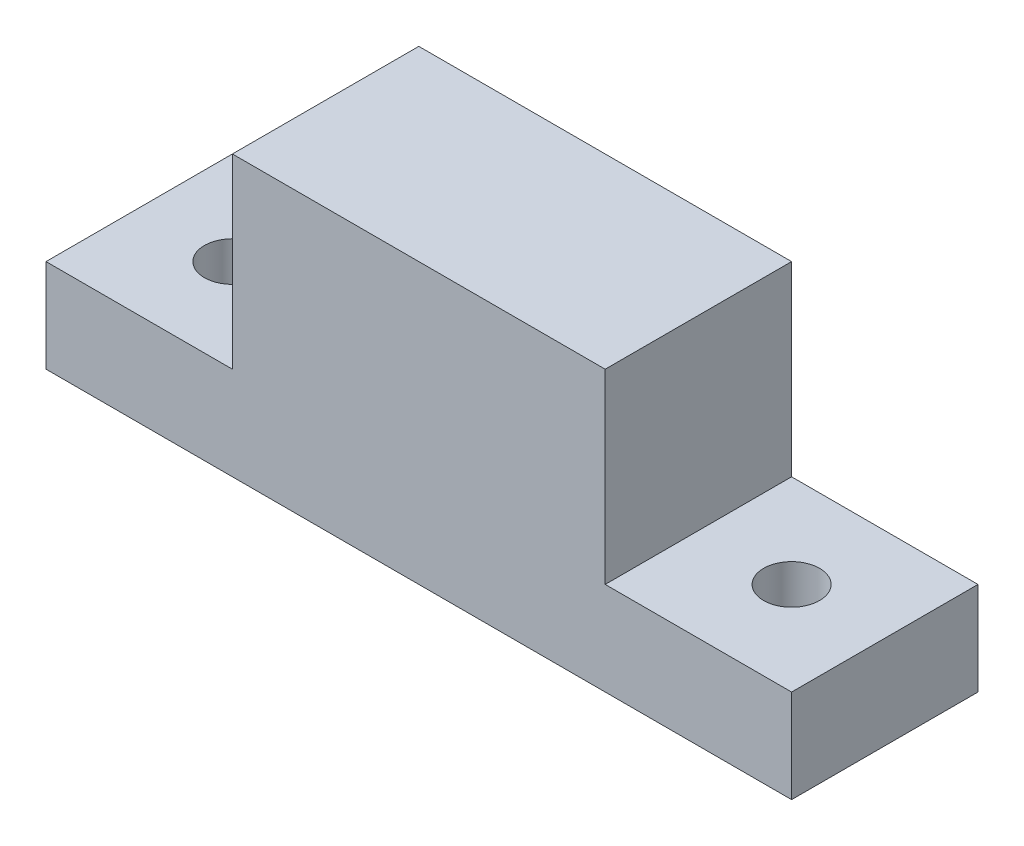
SolidWorks part; units mm, degrees
ref_plane "前视基准面" through (0, 0, 0) normal (0, 0, 1) x (1, 0, 0)
ref_plane "上视基准面" through (0, 0, 0) normal (0, 1, 0) x (1, 0, 0)
ref_plane "右视基准面" through (0, 0, 0) normal (1, 0, 0) x (0, 0, -1)
other "Configuration Table"
sketch "草图1" plane through (0, 0, 0) normal (0, 1, 0) x (1, 0, 0)
  line L0 (-30, 20.1444) -> (-30, -49979.8556) construction
  line L1 (-40, 10) -> (40, 10)
  line L2 (-40, 10) -> (-40, -10)
  line L3 (-40, -10) -> (40, -10)
  line L4 (40, 10) -> (40, -10)
  line L5 (-40, 10) -> (40, -10) construction
  line L6 (-40, -10) -> (40, 10) construction
  line L7 (30, 25.9846) -> (30, -49974.0154) construction
  line L8 (-40, 0) -> (49960, 0) construction
  line L9 (-34.4996, 5) -> (49965.5004, 5) construction
  line L10 (-32.2531, -5) -> (49967.7469, -5) construction
  circle A6 centre (-30, 0) radius 3
  circle A7 centre (30, 0) radius 3
  point P0 (0, 0)
  point P12 (-40, 0)
  dimension "D5" = 5
  dimension "D6" = 5
  dimension "D7" = 6
  dimension "D8" = 6
  dimension "D1" = 80
  dimension "D2" = 20
  dimension "D3" = 10
  dimension "D4" = 10
extrude "凸台-拉伸1" add sketch "草图1" along normal blind 5
sketch "草图2" plane through (0, 5, 0) normal (0, 1, 0) x (1, 0, 0)
  line L0 (-40, -10) -> (40, -10) construction
  line L1 (-20, 10) -> (20, 10)
  line L2 (-20, 10) -> (-20, -10)
  line L3 (-20, -10) -> (20, -10)
  line L4 (20, 10) -> (20, -10)
  line L5 (-20, 10) -> (20, -10) construction
  line L6 (-20, -10) -> (20, 10) construction
  point P0 (0, 0)
  dimension "D1" = 40
extrude "凸台-拉伸2" add sketch "草图2" along normal blind 20
sketch "草图3" plane through (0, 0, 0) normal (0, -1, 0) x (1, 0, 0)
  line L1 (-40, 10) -> (40, 10)
  line L2 (-40, 10) -> (-40, -10)
  line L3 (-40, -10) -> (40, -10)
  line L4 (40, 10) -> (40, -10)
  line L5 (-40, 10) -> (40, -10) construction
  line L6 (-40, -10) -> (40, 10) construction
  circle A0 centre (-30, 0) radius 5
  circle A1 centre (30, 0) radius 5
  circle A2 centre (0, 0) radius 2.5
  point P6 (0, 0)
  dimension "D1" = 5
  dimension "D2" = 10
  dimension "D3" = 10
extrude "凸台-拉伸3" add sketch "草图3" along normal blind 5
